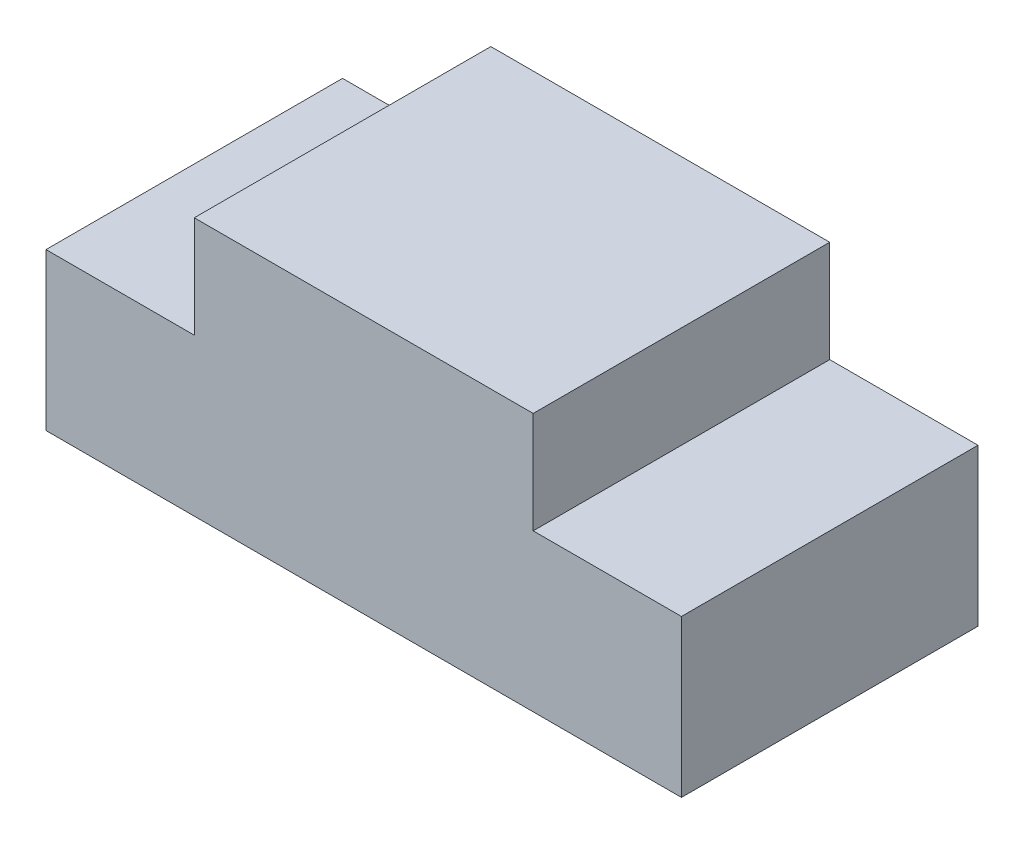
SolidWorks part; units mm, degrees
ref_plane "Front Plane" through (0, 0, 0) normal (0, 0, 1) x (1, 0, 0)
ref_plane "Top Plane" through (0, 0, 0) normal (0, 1, 0) x (1, 0, 0)
ref_plane "Right Plane" through (0, 0, 0) normal (1, 0, 0) x (0, 0, -1)
sketch "Sketch1" plane through (0, 0, 0) normal (0, 0, 1) x (1, 0, 0)
  line L1 (-72.9045, 35.0116) -> (77.0955, 35.0116)
  line L2 (-72.9045, 35.0116) -> (-72.9045, -0.9884)
  line L3 (-72.9045, -0.9884) -> (77.0955, -0.9884)
  line L4 (77.0955, 35.0116) -> (77.0955, -0.9884)
  dimension "D1" = 150
  dimension "D2" = 36
extrude "Boss-Extrude1" add sketch "Sketch1" along normal blind 70
sketch "Sketch3" plane through (0, 35.0116, 0) normal (0, 1, 0) x (1, 0, 0)
  line L0 (-72.9045, -70) -> (-72.9045, 0) construction
  line L1 (-71.9045, -69) -> (76.0955, -69)
  line L2 (-71.9045, -69) -> (-71.9045, -1)
  line L3 (-71.9045, -1) -> (76.0955, -1)
  line L4 (76.0955, -69) -> (76.0955, -1)
  line L5 (77.0955, 0) -> (-72.9045, 0) construction
  line L7 (77.0955, -70) -> (-72.9045, -70) construction
  line L8 (77.0955, -70) -> (77.0955, 0) construction
  dimension "D1" = 1
  dimension "D2" = 1
  dimension "D3" = 1
  dimension "D4" = 1
extrude "Cut-Extrude1" cut sketch "Sketch3" against normal through all
sketch "Sketch4" plane through (0, 35.0116, 0) normal (0, 1, 0) x (1, 0, 0)
  line L0 (2.0955, -70) -> (2.0955, 0) construction
  line L1 (77.0955, -70) -> (-72.9045, -70) construction
  line L2 (77.0955, 0) -> (-72.9045, 0) construction
  line L3 (77.0955, -35) -> (-72.9045, -35) construction
  line L4 (77.0955, -70) -> (77.0955, 0) construction
  line L5 (-72.9045, -70) -> (-72.9045, 0) construction
  line L6 (42.0955, -70) -> (77.0955, -70)
  line L7 (-37.9045, 0) -> (-72.9045, 0)
  line L8 (-37.9045, 0) -> (-37.9045, -70)
  line L9 (-37.9045, -70) -> (-72.9045, -70)
  line L10 (-72.9045, 0) -> (-72.9045, -70)
  line L11 (77.0955, 0) -> (77.0955, -70)
  line L12 (42.0955, 0) -> (77.0955, 0)
  line L13 (42.0955, 0) -> (42.0955, -70)
  dimension "D1" = 40
extrude "Boss-Extrude3" add sketch "Sketch4" along normal blind 1
sketch "Sketch5" plane through (0, 0, 0) normal (0, 0, -1) x (-1, 0, 0)
  line L0 (37.9045, 36.0116) -> (37.9045, 35.0116) construction
  line L1 (-42.0955, 35.0116) -> (37.9045, 35.0116)
  line L2 (-42.0955, 35.0116) -> (-42.0955, 60.0116)
  line L3 (-42.0955, 60.0116) -> (37.9045, 60.0116)
  line L4 (37.9045, 35.0116) -> (37.9045, 60.0116)
  dimension "D1" = 0
  dimension "D2" = 25
extrude "Boss-Extrude4" add sketch "Sketch5" against normal blind 70
sketch "Sketch6" plane through (0, 35.0116, 0) normal (0, -1, 0) x (1, 0, 0)
  line L0 (2.0955, 69) -> (2.0955, 1) construction
  line L1 (-71.9045, 69) -> (76.0955, 69) construction
  line L2 (76.0955, 1) -> (-71.9045, 1) construction
  line L3 (76.0955, 35) -> (-71.9045, 35) construction
  line L4 (76.0955, 69) -> (76.0955, 1) construction
  line L5 (-71.9045, 1) -> (-71.9045, 69) construction
  line L7 (41.0955, 1) -> (-36.9045, 1)
  line L8 (41.0955, 1) -> (41.0955, 69)
  line L9 (41.0955, 69) -> (-36.9045, 69)
  line L10 (-36.9045, 1) -> (-36.9045, 69)
  dimension "D1" = 35
  dimension "D2" = 35
extrude "Cut-Extrude2" cut sketch "Sketch6" against normal blind 24
